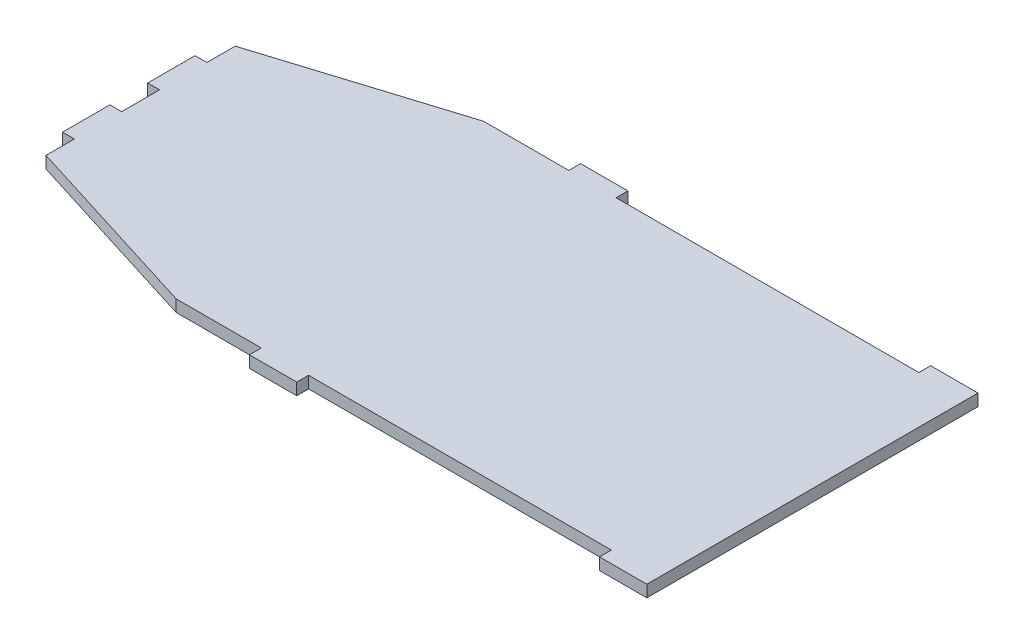
SolidWorks part; units mm, degrees
material "Balsa"
ref_plane "Front Plane" through (0, 0, 0) normal (0, 0, 1) x (1, 0, 0)
ref_plane "Top Plane" through (0, 0, 0) normal (0, 1, 0) x (1, 0, 0)
ref_plane "Right Plane" through (0, 0, 0) normal (1, 0, 0) x (0, 0, -1)
sketch "Sketch1" plane through (0, 0, 0) normal (0, 1, 0) x (1, 0, 0)
  line L0 (-213.0612, 0) -> (213.0612, 0) construction
  line L3 (3.175, 0) -> (3.175, -5.08)
  line L4 (53.975, -41.275) -> (76.835, -41.275)
  line L5 (76.835, -41.275) -> (76.835, -44.45)
  line L6 (76.835, -44.45) -> (89.535, -44.45)
  line L7 (89.535, -44.45) -> (89.535, -41.275)
  line L8 (89.535, -41.275) -> (170.815, -41.275)
  line L13 (183.515, -41.275) -> (183.515, 41.275)
  line L17 (170.815, 41.275) -> (170.815, 44.45)
  line L18 (89.535, 41.275) -> (170.815, 41.275)
  line L19 (89.535, 44.45) -> (89.535, 41.275)
  line L20 (76.835, 44.45) -> (89.535, 44.45)
  line L21 (76.835, 41.275) -> (76.835, 44.45)
  line L22 (53.975, 41.275) -> (76.835, 41.275)
  line L23 (3.175, 0) -> (3.175, 5.08)
  line L26 (183.515, 44.45) -> (183.515, 41.275)
  line L29 (170.815, -41.275) -> (170.815, -44.45)
  line L30 (170.815, -44.45) -> (183.515, -44.45)
  line L31 (183.515, -44.45) -> (183.515, -41.275)
  line L32 (170.815, 44.45) -> (183.515, 44.45)
  line L33 (3.175, -17.78) -> (0, -17.78)
  line L34 (0, -17.78) -> (0, -5.08)
  line L35 (0, -5.08) -> (3.175, -5.08)
  line L36 (3.175, 17.78) -> (0, 17.78)
  line L37 (0, 17.78) -> (0, 5.08)
  line L38 (0, 5.08) -> (3.175, 5.08)
  line L39 (3.175, -17.78) -> (3.175, -25.4)
  line L40 (3.175, 17.78) -> (3.175, 25.4)
  line L41 (3.175, 25.4) -> (53.975, 41.275)
  line L42 (3.175, -25.4) -> (53.975, -41.275)
  point P0 (177.165, 44.45)
  point P4 (0, 0)
  point P20 (183.515, 0)
  dimension "D2" = 88.9
  dimension "D3" = 81.28
  dimension "D4" = 12.7
  dimension "D5" = 12.7
  dimension "D6" = 7.62
  dimension "D7" = 50.8
  dimension "D8" = 3.175
  dimension "D9" = 12.7
  dimension "D10" = 3.175
  dimension "D11" = 22.86
  dimension "D12" = 50.8
extrude "Boss-Extrude1" add sketch "Sketch1" along normal blind 3.175
